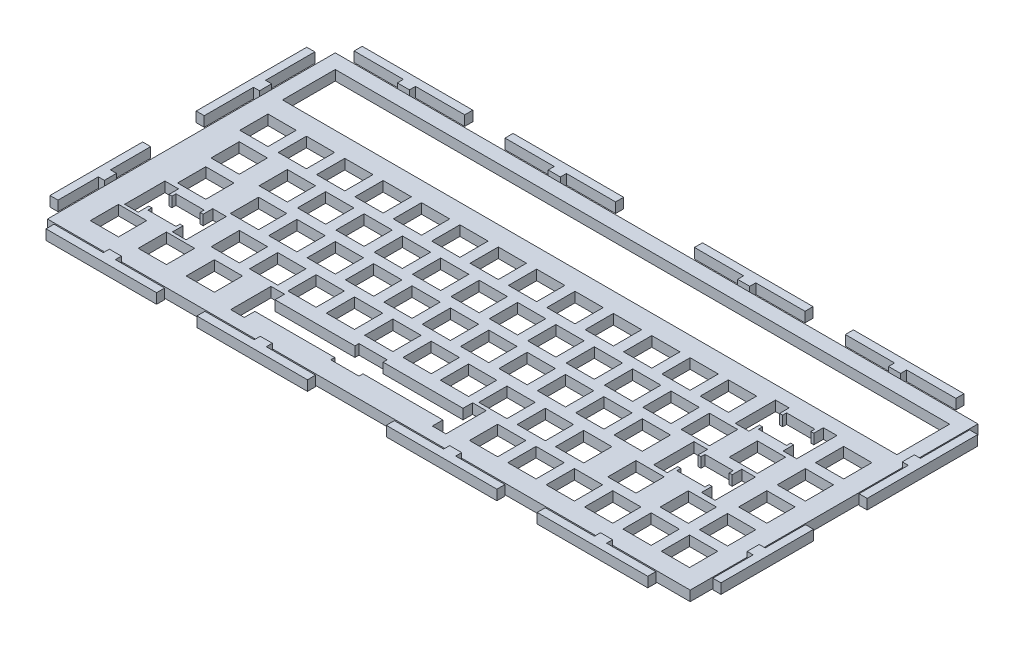
SolidWorks part; units mm, degrees
ref_plane "Front Plane" through (0, 0, 0) normal (0, 0, 1) x (1, 0, 0)
ref_plane "Top Plane" through (0, 0, 0) normal (0, 1, 0) x (1, 0, 0)
ref_plane "Right Plane" through (0, 0, 0) normal (1, 0, 0) x (0, 0, -1)
sketch "Sketch1" plane through (0, 0, 0) normal (0, 1, 0) x (1, 0, 0)
  line L2 (-75.7545, 37.9956) -> (-61.7545, 37.9956)
  line L3 (-94.8265, 37.9956) -> (-80.8265, 37.9956)
  line L4 (-94.8265, 37.9956) -> (-94.8265, 51.9956)
  line L5 (-94.8265, 51.9956) -> (-80.8265, 51.9956)
  line L6 (-80.8265, 37.9956) -> (-80.8265, 51.9956)
  line L7 (-75.7545, 37.9956) -> (-75.7545, 51.9956)
  line L8 (-75.7545, 51.9956) -> (-61.7545, 51.9956)
  line L9 (-61.7545, 37.9956) -> (-61.7545, 51.9956)
  line L10 (133.7495, 37.9956) -> (147.7495, 37.9956)
  line L11 (-37.6545, 37.9956) -> (-23.6545, 37.9956)
  line L12 (-56.7045, 37.9956) -> (-42.7045, 37.9956)
  line L13 (-56.7045, 37.9956) -> (-56.7045, 51.9956)
  line L14 (-56.7045, 51.9956) -> (-42.7045, 51.9956)
  line L15 (-42.7045, 37.9956) -> (-42.7045, 51.9956)
  line L16 (-37.6545, 37.9956) -> (-37.6545, 51.9956)
  line L17 (-37.6545, 51.9956) -> (-23.6545, 51.9956)
  line L18 (-23.6545, 37.9956) -> (-23.6545, 51.9956)
  line L19 (133.7495, 37.9956) -> (133.7495, 51.9956)
  line L20 (133.7495, 51.9956) -> (147.7495, 51.9956)
  line L21 (0.4455, 37.9956) -> (14.4455, 37.9956)
  line L22 (-18.6045, 37.9956) -> (-4.6045, 37.9956)
  line L23 (-18.6045, 37.9956) -> (-18.6045, 51.9956)
  line L24 (-18.6045, 51.9956) -> (-4.6045, 51.9956)
  line L25 (-4.6045, 37.9956) -> (-4.6045, 51.9956)
  line L26 (0.4455, 37.9956) -> (0.4455, 51.9956)
  line L27 (0.4455, 51.9956) -> (14.4455, 51.9956)
  line L28 (14.4455, 37.9956) -> (14.4455, 51.9956)
  line L29 (147.7495, 37.9956) -> (147.7495, 51.9956)
  line L30 (38.5455, 37.9956) -> (52.5455, 37.9956)
  line L31 (19.4955, 37.9956) -> (33.4955, 37.9956)
  line L32 (19.4955, 37.9956) -> (19.4955, 51.9956)
  line L33 (19.4955, 51.9956) -> (33.4955, 51.9956)
  line L34 (33.4955, 37.9956) -> (33.4955, 51.9956)
  line L35 (38.5455, 37.9956) -> (38.5455, 51.9956)
  line L36 (38.5455, 51.9956) -> (52.5455, 51.9956)
  line L37 (52.5455, 37.9956) -> (52.5455, 51.9956)
  line L38 (147.7495, 44.9956) -> (154.1495, 44.9956) construction
  line L39 (167.1835, 18.9456) -> (181.1835, 18.9456)
  line L40 (167.1835, 18.9456) -> (167.1835, 32.9456)
  line L41 (76.6455, 37.9956) -> (90.6455, 37.9956)
  line L42 (57.5955, 37.9956) -> (71.5955, 37.9956)
  line L43 (57.5955, 37.9956) -> (57.5955, 51.9956)
  line L44 (57.5955, 51.9956) -> (71.5955, 51.9956)
  line L45 (71.5955, 37.9956) -> (71.5955, 51.9956)
  line L46 (76.6455, 37.9956) -> (76.6455, 51.9956)
  line L47 (76.6455, 51.9956) -> (90.6455, 51.9956)
  line L48 (90.6455, 37.9956) -> (90.6455, 51.9956)
  line L49 (167.1835, 32.9456) -> (181.1835, 32.9456)
  line L50 (114.7225, 37.9956) -> (128.7225, 37.9956)
  line L51 (95.6955, 37.9956) -> (109.6955, 37.9956)
  line L52 (95.6955, 37.9956) -> (95.6955, 51.9956)
  line L53 (95.6955, 51.9956) -> (109.6955, 51.9956)
  line L54 (109.6955, 37.9956) -> (109.6955, 51.9956)
  line L55 (114.7225, 37.9956) -> (114.7225, 51.9956)
  line L56 (114.7225, 51.9956) -> (128.7225, 51.9956)
  line L57 (128.7225, 37.9956) -> (128.7225, 51.9956)
  line L58 (181.1835, 18.9456) -> (181.1835, 32.9456)
  line L59 (157.3735, 25.9456) -> (167.1835, 25.9456) construction
  line L73 (162.3995, 52.2456) -> (176.3995, 52.2456)
  line L75 (176.3995, 38.2456) -> (162.3995, 38.2456)
  line L77 (176.3995, 52.2456) -> (176.3995, 50.2456)
  line L78 (176.3995, 50.2456) -> (177.8995, 50.2456)
  line L79 (177.8995, 50.2456) -> (177.8995, 54.9956)
  line L80 (177.8995, 54.9956) -> (184.6495, 54.9956)
  line L81 (184.6495, 54.9956) -> (184.6495, 34.9956)
  line L82 (184.6495, 34.9956) -> (177.8995, 34.9956)
  line L83 (177.8995, 34.9956) -> (177.8995, 40.2456)
  line L84 (177.8995, 40.2456) -> (176.3995, 40.2456)
  line L85 (176.3995, 40.2456) -> (176.3995, 38.2456)
  line L86 (162.3995, 52.2456) -> (162.3995, 50.2456)
  line L87 (160.8995, 54.9956) -> (160.8995, 50.2456)
  line L88 (160.8995, 50.2456) -> (162.3995, 50.2456)
  line L89 (160.8995, 54.9956) -> (154.1495, 54.9956)
  line L90 (154.1495, 54.9956) -> (154.1495, 34.9956)
  line L91 (154.1495, 34.9956) -> (160.8995, 34.9956)
  line L92 (160.8995, 34.9956) -> (160.8995, 40.2456)
  line L93 (160.8995, 40.2456) -> (162.3995, 40.2456)
  line L94 (162.3995, 40.2456) -> (162.3995, 38.2456)
  line L116 (-47.1265, 18.9456) -> (-33.1265, 18.9456)
  line L117 (-66.1765, 18.9456) -> (-52.1765, 18.9456)
  line L118 (-66.1765, 18.9456) -> (-66.1765, 32.9456)
  line L119 (-66.1765, 32.9456) -> (-52.1765, 32.9456)
  line L120 (-52.1765, 18.9456) -> (-52.1765, 32.9456)
  line L121 (-47.1265, 18.9456) -> (-47.1265, 32.9456)
  line L122 (-47.1265, 32.9456) -> (-33.1265, 32.9456)
  line L123 (-33.1265, 18.9456) -> (-33.1265, 32.9456)
  line L125 (-9.0515, 18.9456) -> (4.9485, 18.9456)
  line L126 (-28.0765, 18.9456) -> (-14.0765, 18.9456)
  line L127 (-28.0765, 18.9456) -> (-28.0765, 32.9456)
  line L128 (-28.0765, 32.9456) -> (-14.0765, 32.9456)
  line L129 (-14.0765, 18.9456) -> (-14.0765, 32.9456)
  line L130 (-9.0515, 18.9456) -> (-9.0515, 32.9456)
  line L131 (-9.0515, 32.9456) -> (4.9485, 32.9456)
  line L132 (4.9485, 18.9456) -> (4.9485, 32.9456)
  line L135 (29.0735, 18.9456) -> (43.0735, 18.9456)
  line L136 (9.9485, 18.9456) -> (23.9485, 18.9456)
  line L137 (9.9485, 18.9456) -> (9.9485, 32.9456)
  line L138 (9.9485, 32.9456) -> (23.9485, 32.9456)
  line L139 (23.9485, 18.9456) -> (23.9485, 32.9456)
  line L140 (29.0735, 18.9456) -> (29.0735, 32.9456)
  line L141 (29.0735, 32.9456) -> (43.0735, 32.9456)
  line L142 (43.0735, 18.9456) -> (43.0735, 32.9456)
  line L144 (67.1485, 18.9456) -> (81.1485, 18.9456)
  line L145 (48.1235, 18.9456) -> (62.1235, 18.9456)
  line L146 (48.1235, 18.9456) -> (48.1235, 32.9456)
  line L147 (48.1235, 32.9456) -> (62.1235, 32.9456)
  line L148 (62.1235, 18.9456) -> (62.1235, 32.9456)
  line L149 (67.1485, 18.9456) -> (67.1485, 32.9456)
  line L150 (67.1485, 32.9456) -> (81.1485, 32.9456)
  line L151 (81.1485, 18.9456) -> (81.1485, 32.9456)
  line L152 (159.9865, 14.1456) -> (173.9865, 14.1456)
  line L153 (-42.3635, -0.1044) -> (-28.3635, -0.1044)
  line L154 (-61.4135, -0.1044) -> (-47.4135, -0.1044)
  line L155 (105.2735, 18.9456) -> (119.2735, 18.9456)
  line L156 (86.2235, 18.9456) -> (100.2235, 18.9456)
  line L157 (86.2235, 18.9456) -> (86.2235, 32.9456)
  line L158 (86.2235, 32.9456) -> (100.2235, 32.9456)
  line L159 (100.2235, 18.9456) -> (100.2235, 32.9456)
  line L160 (105.2735, 18.9456) -> (105.2735, 32.9456)
  line L161 (105.2735, 32.9456) -> (119.2735, 32.9456)
  line L162 (119.2735, 18.9456) -> (119.2735, 32.9456)
  line L163 (-61.4135, -0.1044) -> (-61.4135, 13.8956)
  line L172 (-94.8265, 37.9956) -> (-94.8265, 32.9456) construction
  line L173 (-61.4135, 13.8956) -> (-47.4135, 13.8956)
  line L174 (-47.4135, -0.1044) -> (-47.4135, 13.8956)
  line L175 (-90.0635, 18.9456) -> (-76.0635, 18.9456)
  line L176 (-90.0635, 18.9456) -> (-90.0635, 32.9456)
  line L177 (-90.0635, 32.9456) -> (-76.0635, 32.9456)
  line L178 (-76.0635, 18.9456) -> (-76.0635, 32.9456)
  line L179 (-94.8265, 32.9456) -> (-90.0635, 32.9456) construction
  line L180 (124.3235, 18.9456) -> (138.3235, 18.9456)
  line L185 (124.3235, 18.9456) -> (124.3235, 32.9456)
  line L186 (124.3235, 32.9456) -> (138.3235, 32.9456)
  line L187 (138.3235, 18.9456) -> (138.3235, 32.9456)
  line L188 (-42.3635, -0.1044) -> (-42.3635, 13.8956)
  line L189 (143.3735, 18.9456) -> (157.3735, 18.9456)
  line L190 (143.3735, 18.9456) -> (143.3735, 32.9456)
  line L191 (143.3735, 32.9456) -> (157.3735, 32.9456)
  line L192 (157.3735, 18.9456) -> (157.3735, 32.9456)
  line L193 (-42.3635, 13.8956) -> (-28.3635, 13.8956)
  line L194 (-28.3635, -0.1044) -> (-28.3635, 13.8956)
  line L195 (-4.2635, -0.1044) -> (9.7365, -0.1044)
  line L196 (-23.3135, -0.1044) -> (-9.3135, -0.1044)
  line L197 (-23.3135, -0.1044) -> (-23.3135, 13.8956)
  line L198 (-23.3135, 13.8956) -> (-9.3135, 13.8956)
  line L199 (-9.3135, -0.1044) -> (-9.3135, 13.8956)
  line L200 (-4.2635, -0.1044) -> (-4.2635, 13.8956)
  line L201 (-4.2635, 13.8956) -> (9.7365, 13.8956)
  line L202 (9.7365, -0.1044) -> (9.7365, 13.8956)
  line L203 (33.8365, -0.1044) -> (47.8365, -0.1044)
  line L204 (14.7865, -0.1044) -> (28.7865, -0.1044)
  line L205 (14.7865, -0.1044) -> (14.7865, 13.8956)
  line L206 (14.7865, 13.8956) -> (28.7865, 13.8956)
  line L207 (28.7865, -0.1044) -> (28.7865, 13.8956)
  line L208 (33.8365, -0.1044) -> (33.8365, 13.8956)
  line L209 (33.8365, 13.8956) -> (47.8365, 13.8956)
  line L210 (47.8365, -0.1044) -> (47.8365, 13.8956)
  line L211 (71.9365, -0.1044) -> (85.9365, -0.1044)
  line L212 (52.8865, -0.1044) -> (66.8865, -0.1044)
  line L213 (52.8865, -0.1044) -> (52.8865, 13.8956)
  line L214 (52.8865, 13.8956) -> (66.8865, 13.8956)
  line L215 (66.8865, -0.1044) -> (66.8865, 13.8956)
  line L216 (71.9365, -0.1044) -> (71.9365, 13.8956)
  line L217 (71.9365, 13.8956) -> (85.9365, 13.8956)
  line L218 (85.9365, -0.1044) -> (85.9365, 13.8956)
  line L219 (110.0365, -0.1044) -> (124.0365, -0.1044)
  line L220 (90.9865, -0.1044) -> (104.9865, -0.1044)
  line L221 (90.9865, -0.1044) -> (90.9865, 13.8956)
  line L222 (90.9865, 13.8956) -> (104.9865, 13.8956)
  line L223 (104.9865, -0.1044) -> (104.9865, 13.8956)
  line L224 (110.0365, -0.1044) -> (110.0365, 13.8956)
  line L225 (110.0365, 13.8956) -> (124.0365, 13.8956)
  line L226 (124.0365, -0.1044) -> (124.0365, 13.8956)
  line L227 (-87.6075, -0.1044) -> (-73.6075, -0.1044)
  line L228 (-87.6075, -0.1044) -> (-87.6075, 13.8956)
  line L229 (-87.6075, 13.8956) -> (-73.6075, 13.8956)
  line L230 (-73.6075, -0.1044) -> (-73.6075, 13.8956)
  line L231 (-90.0635, 18.9456) -> (-90.0635, 13.8956) construction
  line L232 (129.0865, -0.1044) -> (143.0865, -0.1044)
  line L233 (129.0865, -0.1044) -> (129.0865, 13.8956)
  line L234 (129.0865, 13.8956) -> (143.0865, 13.8956)
  line L235 (143.0865, -0.1044) -> (143.0865, 13.8956)
  line L240 (-90.0635, 13.8956) -> (-87.6075, 13.8956) construction
  line L241 (173.9865, 0.1456) -> (159.9865, 0.1456)
  line L242 (173.9865, 14.1456) -> (173.9865, 12.1456)
  line L243 (173.9865, 12.1456) -> (175.4865, 12.1456)
  line L244 (175.4865, 12.1456) -> (175.4865, 16.8956)
  line L245 (175.4865, 16.8956) -> (182.2365, 16.8956)
  line L246 (182.2365, 16.8956) -> (182.2365, -3.1044)
  line L247 (182.2365, -3.1044) -> (175.4865, -3.1044)
  line L248 (175.4865, -3.1044) -> (175.4865, 2.1456)
  line L249 (175.4865, 2.1456) -> (173.9865, 2.1456)
  line L250 (173.9865, 2.1456) -> (173.9865, 0.1456)
  line L251 (159.9865, 14.1456) -> (159.9865, 12.1456)
  line L252 (158.4865, 16.8956) -> (158.4865, 12.1456)
  line L253 (158.4865, 12.1456) -> (159.9865, 12.1456)
  line L254 (158.4865, 16.8956) -> (151.7365, 16.8956)
  line L255 (151.7365, 16.8956) -> (151.7365, -3.1044)
  line L256 (151.7365, -3.1044) -> (158.4865, -3.1044)
  line L257 (158.4865, -3.1044) -> (158.4865, 2.1456)
  line L258 (158.4865, 2.1456) -> (159.9865, 2.1456)
  line L259 (159.9865, 2.1456) -> (159.9865, 0.1456)
  line L260 (143.0865, 12.1456) -> (151.7365, 12.1456) construction
  line L262 (-32.8385, -19.1544) -> (-18.8385, -19.1544)
  line L263 (-51.8885, -19.1544) -> (-37.8885, -19.1544)
  line L264 (-51.8885, -19.1544) -> (-51.8885, -5.1544)
  line L265 (-51.8885, -5.1544) -> (-37.8885, -5.1544)
  line L266 (-37.8885, -19.1544) -> (-37.8885, -5.1544)
  line L267 (-32.8385, -19.1544) -> (-32.8385, -5.1544)
  line L268 (-32.8385, -5.1544) -> (-18.8385, -5.1544)
  line L269 (-18.8385, -19.1544) -> (-18.8385, -5.1544)
  line L270 (5.2615, -19.1544) -> (19.2615, -19.1544)
  line L271 (-13.7885, -19.1544) -> (0.2115, -19.1544)
  line L272 (-13.7885, -19.1544) -> (-13.7885, -5.1544)
  line L273 (-13.7885, -5.1544) -> (0.2115, -5.1544)
  line L274 (0.2115, -19.1544) -> (0.2115, -5.1544)
  line L275 (5.2615, -19.1544) -> (5.2615, -5.1544)
  line L276 (5.2615, -5.1544) -> (19.2615, -5.1544)
  line L277 (19.2615, -19.1544) -> (19.2615, -5.1544)
  line L278 (43.3615, -19.1544) -> (57.3615, -19.1544)
  line L279 (24.3115, -19.1544) -> (38.3115, -19.1544)
  line L280 (24.3115, -19.1544) -> (24.3115, -5.1544)
  line L281 (24.3115, -5.1544) -> (38.3115, -5.1544)
  line L282 (38.3115, -19.1544) -> (38.3115, -5.1544)
  line L283 (43.3615, -19.1544) -> (43.3615, -5.1544)
  line L284 (43.3615, -5.1544) -> (57.3615, -5.1544)
  line L285 (57.3615, -19.1544) -> (57.3615, -5.1544)
  line L286 (81.4615, -19.6544) -> (95.4615, -19.6544)
  line L287 (62.4115, -19.6544) -> (76.4115, -19.6544)
  line L288 (62.4115, -19.6544) -> (62.4115, -5.6544)
  line L289 (62.4115, -5.6544) -> (76.4115, -5.6544)
  line L290 (76.4115, -19.6544) -> (76.4115, -5.6544)
  line L291 (81.4615, -19.6544) -> (81.4615, -5.6544)
  line L292 (81.4615, -5.6544) -> (95.4615, -5.6544)
  line L293 (95.4615, -19.6544) -> (95.4615, -5.6544)
  line L294 (119.5615, -19.6544) -> (133.5615, -19.6544)
  line L295 (100.5115, -19.6544) -> (114.5115, -19.6544)
  line L296 (100.5115, -19.6544) -> (100.5115, -5.6544)
  line L297 (100.5115, -5.6544) -> (114.5115, -5.6544)
  line L298 (114.5115, -19.6544) -> (114.5115, -5.6544)
  line L299 (119.5615, -19.6544) -> (119.5615, -5.6544)
  line L300 (119.5615, -5.6544) -> (133.5615, -5.6544)
  line L301 (133.5615, -19.6544) -> (133.5615, -5.6544)
  line L306 (-83.3445, -5.1544) -> (-69.3445, -5.1544)
  line L307 (145.5235, -19.6544) -> (159.5235, -19.6544)
  line L308 (145.5235, -19.6544) -> (145.5235, -5.6544)
  line L309 (145.5235, -5.6544) -> (159.5235, -5.6544)
  line L310 (159.5235, -19.6544) -> (159.5235, -5.6544)
  line L311 (-69.3445, -19.1544) -> (-83.3445, -19.1544)
  line L331 (171.4855, -19.6544) -> (185.4855, -19.6544)
  line L332 (171.4855, -19.6544) -> (171.4855, -5.6544)
  line L333 (171.4855, -5.6544) -> (185.4855, -5.6544)
  line L334 (185.4855, -19.6544) -> (185.4855, -5.6544)
  line L335 (159.5235, -12.6544) -> (171.4855, -12.6544) construction
  line L336 (-61.4135, -0.1044) -> (-61.4135, -5.1544) construction
  line L337 (-61.4135, -5.1544) -> (-51.8885, -5.1544) construction
  line L338 (-104.4215, 94.9896) -> (-117.5239, 94.9896) construction
  line L339 (-97.2765, 61.6456) -> (207.7235, 61.6456)
  line L340 (190.9955, 18.9456) -> (204.9955, 18.9456)
  line L341 (190.9955, 18.9456) -> (190.9955, 32.9456)
  line L342 (190.9955, 32.9456) -> (204.9955, 32.9456)
  line L343 (204.9955, 18.9456) -> (204.9955, 32.9456)
  line L344 (181.1835, 25.9456) -> (190.9955, 25.9456) construction
  line L345 (190.9745, 37.9956) -> (204.9745, 37.9956)
  line L346 (190.9745, 37.9956) -> (190.9745, 51.9956)
  line L347 (190.9745, 51.9956) -> (204.9745, 51.9956)
  line L348 (204.9745, 37.9956) -> (204.9745, 51.9956)
  line L349 (184.6495, 44.9956) -> (190.9745, 44.9956) construction
  line L350 (190.9425, -0.1044) -> (204.9425, -0.1044)
  line L351 (190.9425, -0.1044) -> (190.9425, 13.8956)
  line L352 (190.9425, 13.8956) -> (204.9425, 13.8956)
  line L353 (204.9425, -0.1044) -> (204.9425, 13.8956)
  line L354 (182.2365, 6.8956) -> (190.9425, 6.8956) construction
  line L355 (190.9855, -19.6544) -> (204.9855, -19.6544)
  line L356 (190.9855, -19.6544) -> (190.9855, -5.6544)
  line L357 (190.9855, -5.6544) -> (204.9855, -5.6544)
  line L358 (204.9855, -19.6544) -> (204.9855, -5.6544)
  line L359 (185.4855, -12.6544) -> (190.9855, -12.6544) construction
  line L360 (-69.3445, -5.1544) -> (-69.3445, -7.1544)
  line L361 (-69.3445, -7.1544) -> (-67.8445, -7.1544)
  line L362 (-67.8445, -7.1544) -> (-67.8445, -2.4044)
  line L363 (-67.8445, -2.4044) -> (-61.0945, -2.4044)
  line L364 (-61.0945, -2.4044) -> (-61.0945, -22.4044)
  line L365 (-61.0945, -22.4044) -> (-67.8445, -22.4044)
  line L366 (-67.8445, -22.4044) -> (-67.8445, -17.1544)
  line L367 (-67.8445, -17.1544) -> (-69.3445, -17.1544)
  line L368 (-69.3445, -17.1544) -> (-69.3445, -19.1544)
  line L369 (-83.3445, -5.1544) -> (-83.3445, -7.1544)
  line L370 (-84.8445, -2.4044) -> (-84.8445, -7.1544)
  line L371 (-84.8445, -7.1544) -> (-83.3445, -7.1544)
  line L372 (-84.8445, -2.4044) -> (-91.5945, -2.4044)
  line L373 (-91.5945, -2.4044) -> (-91.5945, -22.4044)
  line L374 (-91.5945, -22.4044) -> (-84.8445, -22.4044)
  line L375 (-84.8445, -22.4044) -> (-84.8445, -17.1544)
  line L376 (-84.8445, -17.1544) -> (-83.3445, -17.1544)
  line L377 (-83.3445, -17.1544) -> (-83.3445, -19.1544)
  line L378 (-93.0945, -37.9544) -> (-79.0945, -37.9544)
  line L379 (-93.0945, -37.9544) -> (-93.0945, -23.9544)
  line L380 (-93.0945, -23.9544) -> (-79.0945, -23.9544)
  line L381 (-79.0945, -37.9544) -> (-79.0945, -23.9544)
  line L382 (-69.2945, -37.9544) -> (-55.2945, -37.9544)
  line L383 (-69.2945, -37.9544) -> (-69.2945, -23.9544)
  line L384 (-69.2945, -23.9544) -> (-55.2945, -23.9544)
  line L385 (-55.2945, -37.9544) -> (-55.2945, -23.9544)
  line L390 (-45.4945, -37.9544) -> (-31.4945, -37.9544)
  line L391 (-45.4945, -37.9544) -> (-45.4945, -23.9544)
  line L392 (-45.4945, -23.9544) -> (-31.4945, -23.9544)
  line L393 (-31.4945, -37.9544) -> (-31.4945, -23.9544)
  line L394 (-55.2945, -23.9544) -> (-45.4945, -23.9544) construction
  line L395 (26.4395, -24.1144) -> (40.4395, -24.1144)
  line L396 (40.4395, -38.1144) -> (26.4395, -38.1144)
  line L397 (40.4395, -24.1144) -> (40.4395, -26.1144)
  line L398 (40.4395, -26.1144) -> (80.1235, -26.1144)
  line L399 (80.1235, -26.1144) -> (80.1235, -21.3644)
  line L400 (80.1235, -21.3644) -> (86.8735, -21.3644)
  line L401 (86.8735, -21.3644) -> (86.8735, -41.3644)
  line L402 (86.8735, -41.3644) -> (80.1235, -41.3644)
  line L403 (80.1235, -41.3644) -> (80.1235, -36.1144)
  line L404 (80.1235, -36.1144) -> (40.4395, -36.1144)
  line L405 (40.4395, -36.1144) -> (40.4395, -38.1144)
  line L406 (26.4395, -24.1144) -> (26.4395, -26.1144)
  line L407 (-13.2445, -21.3644) -> (-13.2445, -26.1144)
  line L408 (-13.2445, -26.1144) -> (26.4395, -26.1144)
  line L409 (-13.2445, -21.3644) -> (-19.9945, -21.3644)
  line L410 (-19.9945, -21.3644) -> (-19.9945, -41.3644)
  line L411 (-19.9945, -41.3644) -> (-13.2445, -41.3644)
  line L412 (-13.2445, -41.3644) -> (-13.2445, -36.1144)
  line L413 (-13.2445, -36.1144) -> (26.4395, -36.1144)
  line L414 (26.4395, -36.1144) -> (26.4395, -38.1144)
  line L415 (95.5435, -38.3644) -> (109.5435, -38.3644)
  line L416 (95.5435, -38.3644) -> (95.5435, -24.3644)
  line L417 (95.5435, -24.3644) -> (109.5435, -24.3644)
  line L418 (109.5435, -38.3644) -> (109.5435, -24.3644)
  line L419 (86.8735, -31.3644) -> (95.5435, -31.3644) construction
  line L420 (114.5935, -38.3644) -> (128.5935, -38.3644)
  line L421 (114.5935, -38.3644) -> (114.5935, -24.3644)
  line L422 (114.5935, -24.3644) -> (128.5935, -24.3644)
  line L423 (128.5935, -38.3644) -> (128.5935, -24.3644)
  line L424 (114.5935, -31.3644) -> (109.5435, -31.3644) construction
  line L425 (133.6435, -38.3644) -> (147.6435, -38.3644)
  line L426 (133.6435, -38.3644) -> (133.6435, -24.3644)
  line L427 (133.6435, -24.3644) -> (147.6435, -24.3644)
  line L428 (147.6435, -38.3644) -> (147.6435, -24.3644)
  line L429 (152.6935, -38.3644) -> (166.6935, -38.3644)
  line L430 (152.6935, -38.3644) -> (152.6935, -24.3644)
  line L431 (152.6935, -24.3644) -> (166.6935, -24.3644)
  line L432 (166.6935, -38.3644) -> (166.6935, -24.3644)
  line L433 (171.7435, -38.3644) -> (185.7435, -38.3644)
  line L434 (171.7435, -38.3644) -> (171.7435, -24.3644)
  line L435 (171.7435, -24.3644) -> (185.7435, -24.3644)
  line L436 (185.7435, -38.3644) -> (185.7435, -24.3644)
  line L437 (190.7935, -38.3644) -> (204.7935, -38.3644)
  line L438 (190.7935, -38.3644) -> (190.7935, -24.3644)
  line L439 (190.7935, -24.3644) -> (204.7935, -24.3644)
  line L440 (204.7935, -38.3644) -> (204.7935, -24.3644)
  line L441 (-97.2765, 61.6456) -> (-97.2765, 87.8456)
  line L442 (-97.2765, 87.8456) -> (207.7235, 87.8456)
  line L443 (207.7235, 61.6456) -> (207.7235, 87.8456)
  line L444 (-104.4215, 94.9896) -> (214.6585, 94.9896)
  line L445 (-104.4215, 94.9896) -> (-104.4215, -47.8854)
  line L446 (-104.4215, -47.8854) -> (214.6585, -47.8854)
  line L447 (214.6585, 94.9896) -> (214.6585, -47.8854)
  line L448 (-117.5239, 94.9896) -> (-117.5239, 25.8096) construction
  line L449 (-104.4215, -47.8854) -> (-117.5239, -47.8854) construction
  line L450 (-117.5239, -47.8854) -> (-117.5239, 14.6046) construction
  line L451 (-150.5498, 25.8096) -> (-98.6233, 25.8096) construction
  line L452 (-150.5498, 14.6046) -> (-97.2765, 14.6046) construction
  line L453 (-104.4215, 94.9896) -> (-104.4215, 60.3996) construction
  point P115 (128.7225, 44.9956)
  point P116 (154.1495, 44.9956)
  dimension "D1" = 14
  dimension "D2" = 20
  dimension "D3" = 4.75
  dimension "D4" = 6.75
  dimension "D5" = 1.5
  dimension "D6" = 2
  dimension "D13" = 14
  dimension "D14" = 14
  dimension "D15" = 5.072
  dimension "D16" = 14
  dimension "D17" = 5.05
  dimension "D18" = 5.05
  dimension "D19" = 14
  dimension "D20" = 4.763
  dimension "D21" = 5.05
  dimension "D22" = 9.887
  dimension "D23" = 26.2
  dimension "D24" = 14
  dimension "D25" = 14
  dimension "D26" = 5.05
  dimension "D27" = 5.05
  dimension "D28" = 5.05
  dimension "D29" = 5.05
  dimension "D30" = 5.05
  dimension "D31" = 5.05
  dimension "D32" = 5.05
  dimension "D33" = 5.05
  dimension "D34" = 5.05
  dimension "D35" = 5.027
  dimension "D36" = 5.05
  dimension "D37" = 5.05
  dimension "D38" = 5.025
  dimension "D39" = 5
  dimension "D40" = 5.125
  dimension "D41" = 5.05
  dimension "D42" = 5.025
  dimension "D43" = 5.075
  dimension "D44" = 5.05
  dimension "D45" = 5.05
  dimension "D46" = 5.027
  dimension "D47" = 14.65
  dimension "D48" = 14
  dimension "D49" = 9.81
  dimension "D50" = 12.194
  dimension "D51" = 5.05
  dimension "D52" = 5.05
  dimension "D53" = 5.05
  dimension "D54" = 5.05
  dimension "D55" = 5.05
  dimension "D56" = 5.05
  dimension "D57" = 5.05
  dimension "D58" = 5.05
  dimension "D59" = 5.05
  dimension "D60" = 5.05
  dimension "D61" = 14
  dimension "D62" = 20
  dimension "D63" = 5.05
  dimension "D64" = 2.456
  dimension "D65" = 4.75
  dimension "D66" = 6.75
  dimension "D67" = 1.5
  dimension "D68" = 2
  dimension "D69" = 16.9
  dimension "D70" = 14
  dimension "D71" = 5.05
  dimension "D72" = 5.05
  dimension "D73" = 5.05
  dimension "D74" = 5.05
  dimension "D75" = 5.05
  dimension "D76" = 5.05
  dimension "D77" = 5.05
  dimension "D78" = 5.05
  dimension "D79" = 5.05
  dimension "D80" = 11.962
  dimension "D81" = 20
  dimension "D82" = 14
  dimension "D83" = 11.962
  dimension "D84" = 14
  dimension "D85" = 14
  dimension "D86" = 9.812
  dimension "D87" = 14
  dimension "D88" = 14.575
  dimension "D89" = 4.75
  dimension "D90" = 14
  dimension "D91" = 6.75
  dimension "D92" = 14
  dimension "D93" = 16.956
  dimension "D94" = 14
  dimension "D95" = 5.5
  dimension "D96" = 5.05
  dimension "D97" = 5.05
  dimension "D98" = 9.525
  dimension "D99" = 1.5
  dimension "D100" = 2
  dimension "D101" = 5.05
  dimension "D102" = 9.206
  dimension "D103" = 5.05
  dimension "D104" = 14
  dimension "D105" = 14
  dimension "D106" = 14
  dimension "D107" = 14
  dimension "D108" = 1.5
  dimension "D109" = 9.8
  dimension "D110" = 5.05
  dimension "D111" = 9.8
  dimension "D112" = 5.05
  dimension "D113" = 5.05
  dimension "D114" = 14
  dimension "D115" = 14
  dimension "D116" = 20
  dimension "D117" = 4.75
  dimension "D118" = 6.75
  dimension "D119" = 39.684
  dimension "D120" = 2
  dimension "D121" = 5.05
  dimension "D122" = 11.5
  dimension "D123" = 14
  dimension "D124" = 8.67
  dimension "D125" = 5.25
  dimension "D126" = 14
  dimension "D127" = 5.05
  dimension "D128" = 14
  dimension "D129" = 14
  dimension "D130" = 14
  dimension "D131" = 14
  dimension "D132" = 5.05
  dimension "D133" = 5.05
  dimension "D134" = 5.05
  dimension "D135" = 5.05
  dimension "D136" = 4.8
  dimension "D137" = 5.25
  dimension "D138" = 5.25
  dimension "D139" = 5.25
  dimension "D140" = 305
  dimension "D141" = 9.65
  dimension "D142" = 142.875
  dimension "D143" = 319.08
  dimension "D144" = 7.144
  dimension "D145" = 7.145
  dimension "D146" = 2.45
  dimension "D147" = 69.18
  dimension "D148" = 62.49
extrude "Boss-Extrude2" add sketch "Sketch1" along normal mid plane 5
sketch "Sketch2" plane through (0, 2.5, 0) normal (0, 1, 0) x (1, 0, 0)
  line L0 (-104.4215, 25.7896) -> (-104.4215, 14.6146) construction
  line L1 (-104.4215, -47.8854) -> (-104.4215, 14.6146) construction
  line L2 (-104.4215, 94.9896) -> (-104.4215, -47.8854) construction
  line L3 (-104.4215, 94.9896) -> (-104.4215, 25.7896) construction
  line L4 (-104.4215, 60.3896) -> (-192.4203, 60.3896) construction
  line L5 (-104.4215, 63.3896) -> (-104.4215, 57.3896)
  line L6 (-104.4215, 63.3896) -> (-107.4215, 63.3896)
  line L7 (-104.4215, 57.3896) -> (-107.4215, 57.3896)
  line L8 (-107.4215, 63.3896) -> (-107.4215, 87.8456)
  line L9 (-107.4215, 57.3896) -> (-107.4215, 32.9456)
  line L10 (-107.4215, 87.8456) -> (-111.4215, 87.8456)
  line L11 (-111.4215, 87.8456) -> (-111.4215, 32.9456)
  line L12 (-111.4215, 32.9456) -> (-107.4215, 32.9456)
  line L13 (207.7235, 87.8456) -> (-97.2765, 87.8456) construction
  line L14 (-107.4215, 20.2021) -> (-104.4215, 20.2021) construction
  line L15 (-76.0635, 32.9456) -> (-90.0635, 32.9456) construction
  line L16 (-107.4215, 31.2421) -> (-107.4215, 9.1621) construction
  line L17 (-104.4215, -13.6354) -> (-104.4215, -19.6354)
  line L18 (-104.4215, -13.6354) -> (-107.4215, -13.6354)
  line L19 (-104.4215, -19.6354) -> (-107.4215, -19.6354)
  line L20 (-107.4215, -13.6354) -> (-107.4215, 6.3646)
  line L21 (-107.4215, 6.3646) -> (-111.4215, 6.3646)
  line L22 (-111.4215, 6.3646) -> (-111.4215, -39.6354)
  line L23 (-111.4215, -39.6354) -> (-107.4215, -39.6354)
  line L24 (-107.4215, -39.6354) -> (-107.4215, -19.6354)
  line L25 (214.6585, 14.5646) -> (214.6585, -47.8854) construction
  line L26 (55.1185, 125.0696) -> (55.1185, -78.0627) construction
  line L27 (221.6585, -39.6354) -> (217.6585, -39.6354)
  line L28 (221.6585, 6.3646) -> (221.6585, -39.6354)
  line L29 (217.6585, 6.3646) -> (221.6585, 6.3646)
  line L30 (217.6585, -13.6354) -> (217.6585, 6.3646)
  line L31 (214.6585, -13.6354) -> (217.6585, -13.6354)
  line L32 (214.6585, -13.6354) -> (214.6585, -19.6354)
  line L33 (214.6585, -19.6354) -> (217.6585, -19.6354)
  line L34 (217.6585, -39.6354) -> (217.6585, -19.6354)
  line L35 (214.6585, 63.3896) -> (217.6585, 63.3896)
  line L36 (217.6585, 63.3896) -> (217.6585, 87.8456)
  line L37 (217.6585, 87.8456) -> (221.6585, 87.8456)
  line L38 (221.6585, 87.8456) -> (221.6585, 32.9456)
  line L39 (221.6585, 32.9456) -> (217.6585, 32.9456)
  line L40 (217.6585, 57.3896) -> (217.6585, 32.9456)
  line L41 (214.6585, 57.3896) -> (217.6585, 57.3896)
  line L42 (214.6585, 63.3896) -> (214.6585, 57.3896)
  line L43 (214.6585, -47.8854) -> (214.6585, 94.9896) construction
  line L44 (214.6585, 94.9896) -> (214.6585, 25.7896) construction
  line L45 (214.6585, 25.7896) -> (214.6585, 14.5646) construction
  line L46 (214.6585, 20.1771) -> (217.6585, 20.1771) construction
  line L47 (217.6585, 31.2421) -> (217.6585, 9.1621) construction
  line L48 (55.1185, 94.9896) -> (55.1185, -47.8854) construction
  line L49 (214.6585, 94.9896) -> (-104.4215, 94.9896) construction
  line L50 (-104.4215, -47.8854) -> (214.6585, -47.8854) construction
  line L51 (55.1185, 23.5034) -> (270.1989, 23.5034) construction
  line L52 (55.1185, 23.5034) -> (-168.679, 23.5034) construction
  line L53 (214.6585, 94.9896) -> (56.9085, 94.9896) construction
  line L54 (-104.4215, 94.9896) -> (45.7235, 94.9896) construction
  line L55 (45.7235, 94.9896) -> (56.9085, 94.9896) construction
  line L56 (51.316, 94.9896) -> (51.316, 98.9896) construction
  line L57 (40.276, 98.9896) -> (62.356, 98.9896) construction
  line L58 (170.2335, 94.9896) -> (176.2335, 94.9896)
  line L59 (176.2335, 94.9896) -> (176.2335, 97.9896)
  line L60 (176.2335, 97.9896) -> (200.6835, 97.9896)
  line L61 (200.6835, 97.9896) -> (200.6835, 101.9896)
  line L62 (200.6835, 101.9896) -> (145.7835, 101.9896)
  line L63 (145.7835, 101.9896) -> (145.7835, 97.9896)
  line L64 (145.7835, 97.9896) -> (170.2335, 97.9896)
  line L65 (170.2335, 97.9896) -> (170.2335, 94.9896)
  line L66 (95.3335, 94.9896) -> (101.3335, 94.9896)
  line L67 (101.3335, 94.9896) -> (101.3335, 97.9896)
  line L68 (101.3335, 97.9896) -> (125.7835, 97.9896)
  line L69 (125.7835, 97.9896) -> (125.7835, 101.9896)
  line L70 (125.7835, 101.9896) -> (70.8835, 101.9896)
  line L71 (70.8835, 101.9896) -> (70.8835, 97.9896)
  line L72 (70.8835, 97.9896) -> (95.3335, 97.9896)
  line L73 (95.3335, 97.9896) -> (95.3335, 94.9896)
  line L74 (125.7835, 99.9896) -> (145.7835, 99.9896) construction
  line L75 (135.7835, 94.9896) -> (135.7835, 104.9896) construction
  line L76 (-43.1515, 97.9896) -> (-67.6015, 97.9896)
  line L77 (-43.1515, 101.9896) -> (-43.1515, 97.9896)
  line L78 (-98.0515, 101.9896) -> (-43.1515, 101.9896)
  line L79 (-98.0515, 97.9896) -> (-98.0515, 101.9896)
  line L80 (-73.6015, 97.9896) -> (-98.0515, 97.9896)
  line L81 (-73.6015, 94.9896) -> (-73.6015, 97.9896)
  line L82 (-67.6015, 94.9896) -> (-73.6015, 94.9896)
  line L83 (-67.6015, 97.9896) -> (-67.6015, 94.9896)
  line L84 (7.2985, 97.9896) -> (7.2985, 94.9896)
  line L85 (31.7485, 97.9896) -> (7.2985, 97.9896)
  line L86 (31.7485, 101.9896) -> (31.7485, 97.9896)
  line L87 (-23.1515, 101.9896) -> (31.7485, 101.9896)
  line L88 (-23.1515, 97.9896) -> (-23.1515, 101.9896)
  line L89 (1.2985, 97.9896) -> (-23.1515, 97.9896)
  line L90 (1.2985, 94.9896) -> (1.2985, 97.9896)
  line L91 (7.2985, 94.9896) -> (1.2985, 94.9896)
  line L92 (145.7835, -50.9827) -> (170.2335, -50.9827)
  line L93 (145.7835, -54.9827) -> (145.7835, -50.9827)
  line L94 (200.6835, -54.9827) -> (145.7835, -54.9827)
  line L95 (200.6835, -50.9827) -> (200.6835, -54.9827)
  line L96 (176.2335, -50.9827) -> (200.6835, -50.9827)
  line L97 (176.2335, -47.9827) -> (176.2335, -50.9827)
  line L98 (170.2335, -47.9827) -> (176.2335, -47.9827)
  line L99 (170.2335, -50.9827) -> (170.2335, -47.9827)
  line L100 (95.3335, -50.9827) -> (95.3335, -47.9827)
  line L101 (70.8835, -50.9827) -> (95.3335, -50.9827)
  line L102 (70.8835, -54.9827) -> (70.8835, -50.9827)
  line L103 (125.7835, -54.9827) -> (70.8835, -54.9827)
  line L104 (125.7835, -50.9827) -> (125.7835, -54.9827)
  line L105 (101.3335, -50.9827) -> (125.7835, -50.9827)
  line L106 (101.3335, -47.9827) -> (101.3335, -50.9827)
  line L107 (95.3335, -47.9827) -> (101.3335, -47.9827)
  line L108 (31.7485, -50.9827) -> (7.2985, -50.9827)
  line L109 (31.7485, -54.9827) -> (31.7485, -50.9827)
  line L110 (-23.1515, -54.9827) -> (31.7485, -54.9827)
  line L111 (-23.1515, -50.9827) -> (-23.1515, -54.9827)
  line L112 (1.2985, -50.9827) -> (-23.1515, -50.9827)
  line L113 (1.2985, -47.9827) -> (1.2985, -50.9827)
  line L114 (7.2985, -47.9827) -> (1.2985, -47.9827)
  line L115 (7.2985, -50.9827) -> (7.2985, -47.9827)
  line L116 (-43.1515, -54.9827) -> (-43.1515, -50.9827)
  line L117 (-98.0515, -54.9827) -> (-43.1515, -54.9827)
  line L118 (-98.0515, -50.9827) -> (-98.0515, -54.9827)
  line L119 (-73.6015, -50.9827) -> (-98.0515, -50.9827)
  line L120 (-73.6015, -47.9827) -> (-73.6015, -50.9827)
  line L121 (-67.6015, -47.9827) -> (-73.6015, -47.9827)
  line L122 (-67.6015, -50.9827) -> (-67.6015, -47.9827)
  line L123 (-43.1515, -50.9827) -> (-67.6015, -50.9827)
  line L124 (214.6585, -47.8854) -> (56.9135, -47.8854) construction
  line L125 (-104.4215, 94.9896) -> (-104.4215, 96.9896) construction
  line L126 (-104.4215, -47.8854) -> (45.7225, -47.8854) construction
  line L127 (45.7225, -47.8854) -> (56.9135, -47.8854) construction
  line L128 (51.318, -47.8854) -> (51.318, -52.8854) construction
  line L129 (40.276, -52.8854) -> (62.356, -52.8854) construction
  line L130 (-104.4215, 96.9896) -> (-90.2825, 96.9896) construction
  line L131 (-90.2825, 96.9896) -> (-81.3425, 96.9896) construction
  line L132 (55.1185, 125.0696) -> (-104.4215, 125.0696) construction
  line L133 (258.1815, 94.9896) -> (258.1815, -47.8854) construction
  line L134 (-104.4215, 94.9896) -> (-104.4215, 63.3896) construction
  point P17 (-104.4215, 60.3896)
  point P21 (-104.4215, 60.3896)
  point P28 (-104.4215, 20.2021)
  point P31 (-104.4215, -16.6354)
  point P34 (-104.4215, -16.6354)
  point P84 (51.316, 98.9896)
  point P103 (145.7835, 99.9896)
  point P106 (135.7835, 99.9896)
  point P107 (135.7835, 99.9896)
  dimension "D1" = 69.2
  dimension "D2" = 62.5
  dimension "D3" = 3
  dimension "D4" = 6
  dimension "D5" = 0
  dimension "D6" = 0
  dimension "D7" = 22.08
  dimension "D8" = 3
  dimension "D9" = 6
  dimension "D10" = 3
  dimension "D11" = 20
  dimension "D12" = 4
  dimension "D13" = 4
  dimension "D14" = 62.45
  dimension "D15" = 69.2
  dimension "D16" = 22.08
  dimension "D17" = 157.75
  dimension "D18" = 150.145
  dimension "D19" = 4
  dimension "D20" = 22.08
  dimension "D21" = 6
  dimension "D22" = 3
  dimension "D23" = 4
  dimension "D24" = 54.9
  dimension "D25" = 6
  dimension "D26" = 3
  dimension "D27" = 4
  dimension "D28" = 54.9
  dimension "D29" = 20
  dimension "D30" = 10
  dimension "D31" = 157.745
  dimension "D32" = 150.144
  dimension "D33" = 5
  dimension "D34" = 22.08
  dimension "D35" = 2
  dimension "D36" = 14.139
  dimension "D37" = 8.94
  dimension "D38" = 159.54
  dimension "D39" = 142.875
  dimension "D40" = 14.8425
  dimension "D41" = 14.8425
extrude "Boss-Extrude3" add sketch "Sketch2" along normal mid plane 5
sketch "Sketch3" plane through (-104.4215, 0, 0) normal (-1, 0, 0) x (0, 0, 1)
  line L0 (-94.9896, -2.5) -> (47.8854, -2.5) construction
  dimension "D1" = 2.5
